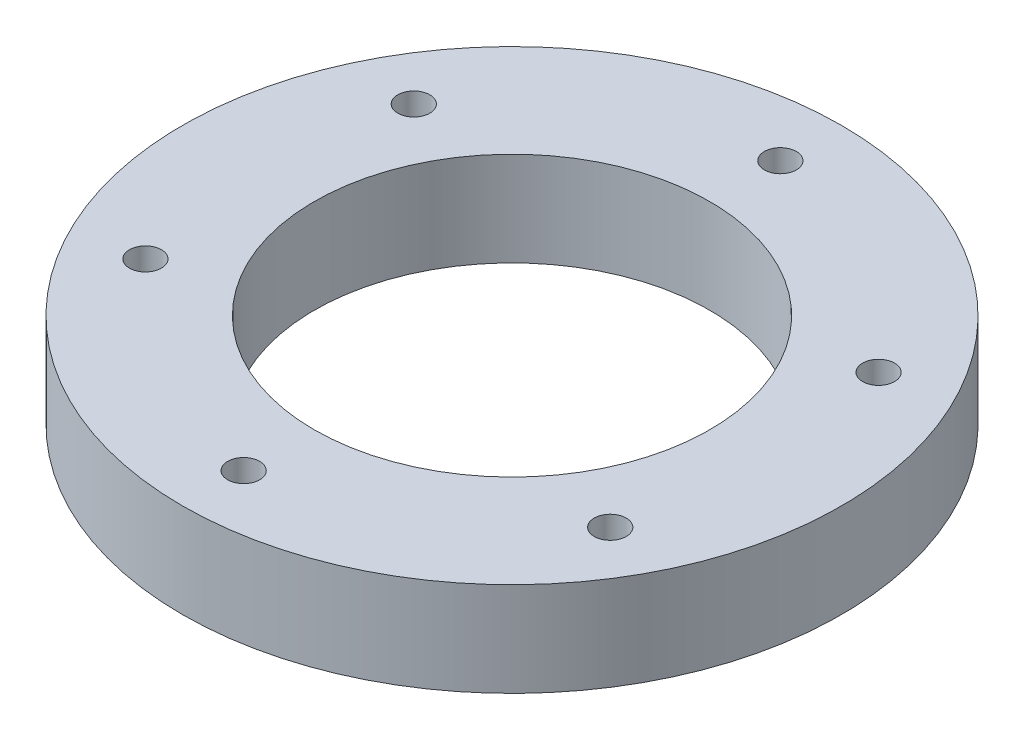
SolidWorks part; units mm, degrees
ref_plane "前视基准面" through (0, 0, 0) normal (0, 0, 1) x (1, 0, 0)
ref_plane "上视基准面" through (0, 0, 0) normal (0, 1, 0) x (1, 0, 0)
ref_plane "右视基准面" through (0, 0, 0) normal (1, 0, 0) x (0, 0, -1)
other "Configuration Table"
sketch "草图1" plane through (0, 0, 0) normal (0, 1, 0) x (1, 0, 0)
  circle A0 centre (0, 0) radius 35
  circle A1 centre (0, 0) radius 21
  dimension "D1" = 70
  dimension "D2" = 42
extrude "凸台-拉伸1" add sketch "草图1" along normal blind 10
sketch "草图2" plane through (0, 10, 0) normal (0, 1, 0) x (1, 0, 0)
  line L0 (0, 0) -> (0, 28.5) construction
  circle A0 centre (0, 28.5) radius 1.7
  circle A1 centre (24.6817, 14.25) radius 1.7
  circle A2 centre (24.6817, -14.25) radius 1.7
  circle A3 centre (0, -28.5) radius 1.7
  circle A4 centre (-24.6817, -14.25) radius 1.7
  circle A5 centre (-24.6817, 14.25) radius 1.7
  point P16 (0, 0)
  dimension "D2" = 3.4
  dimension "D1" = 28.5
  dimension "D3" = 6
extrude "切除-拉伸1" cut sketch "草图2" against normal blind 10
